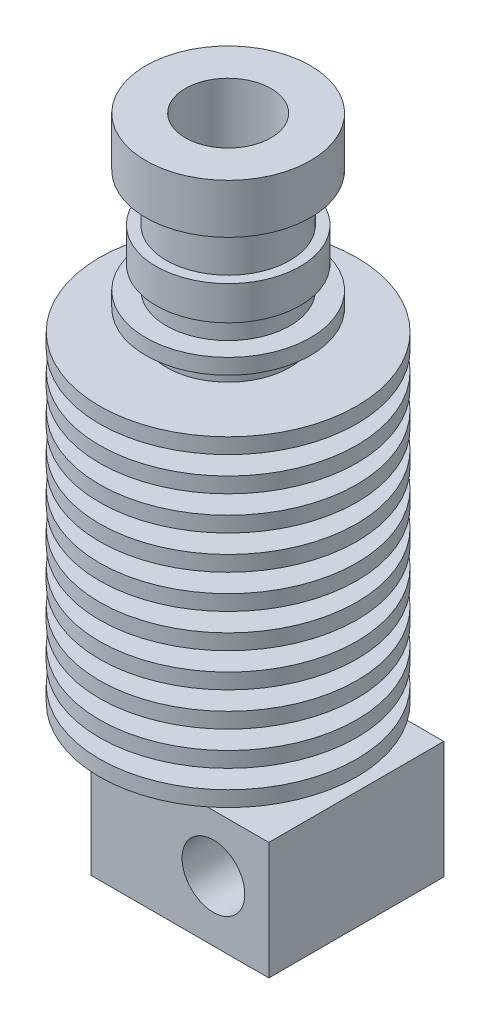
SolidWorks part; units mm, degrees
ref_plane "Front Plane" through (0, 0, 0) normal (0, 0, 1) x (1, 0, 0)
ref_plane "Top Plane" through (0, 0, 0) normal (0, 1, 0) x (1, 0, 0)
ref_plane "Right Plane" through (0, 0, 0) normal (1, 0, 0) x (0, 0, -1)
sketch "Sketch1" plane through (0, 0, 0) normal (0, 0, 1) x (1, 0, 0)
  line L0 (0, -1005.6554) -> (0, 48994.3446) construction
  line L1 (-2, -15.9255) -> (-2, -28.8164)
  line L2 (-8, 28.8745) -> (-6, 28.8745)
  line L3 (-8, 33.6745) -> (0, 33.6745)
  line L4 (-8, 33.6745) -> (-8, 28.8745)
  line L5 (-4, -32.8366) -> (-0.943, -34.9981)
  line L6 (0, 33.6745) -> (0, -33.6745)
  line L7 (-6, 28.8745) -> (-6, 24.2745)
  line L8 (-6, 24.2745) -> (-7, 24.2745)
  line L9 (-7, 24.2745) -> (-7, 20.9745)
  line L10 (-7, 20.9745) -> (-6, 20.9745)
  line L11 (-6, 20.9745) -> (-6, 18.7745)
  line L12 (-6, 18.7745) -> (-8, 18.7745)
  line L13 (-8, 18.7745) -> (-8, 17.2745)
  line L14 (-8, 17.2745) -> (-6, 17.2745)
  line L15 (-6, 17.2745) -> (-6, 15.2745)
  line L16 (-6, 15.2745) -> (-12.5, 15.2745)
  line L17 (-12.5, 15.2745) -> (-12.5, 13.7745)
  line L18 (-12.5, 13.7745) -> (-7.5, 13.7745)
  line L19 (-7.5, 13.7745) -> (-7.5, 11.9745)
  line L20 (-7.5, 11.9745) -> (-12.5, 11.9745)
  line L21 (-12.5, 11.9745) -> (-12.5, 10.4745)
  line L22 (-12.5, 10.4745) -> (-7.5, 10.4745)
  line L23 (-7.5, 10.4745) -> (-7.5, 8.6745)
  line L24 (-7.5, 8.6745) -> (-12.5, 8.6745)
  line L25 (-12.5, 8.6745) -> (-12.5, 7.1745)
  line L26 (-12.5, 7.1745) -> (-7.5, 7.1745)
  line L27 (-7.5, 7.1745) -> (-7.5, 5.3745)
  line L28 (-7.5, 5.3745) -> (-12.5, 5.3745)
  line L29 (-12.5, 5.3745) -> (-12.5, 3.8745)
  line L30 (-12.5, 3.8745) -> (-7.5, 3.8745)
  line L31 (-7.5, 3.8745) -> (-7.5, 2.0745)
  line L32 (-7.5, 2.0745) -> (-12.5, 2.0745)
  line L33 (-12.5, 2.0745) -> (-12.5, 0.5745)
  line L34 (-12.5, 0.5745) -> (-7.5, 0.5745)
  line L35 (-7.5, 0.5745) -> (-7.5, -1.2255)
  line L36 (-7.5, -1.2255) -> (-12.5, -1.2255)
  line L37 (-12.5, -1.2255) -> (-12.5, -2.7255)
  line L38 (-12.5, -2.7255) -> (-7.5, -2.7255)
  line L39 (-7.5, -2.7255) -> (-7.5, -4.5255)
  line L40 (-7.5, -4.5255) -> (-12.5, -4.5255)
  line L41 (-12.5, -4.5255) -> (-12.5, -6.0255)
  line L42 (-12.5, -6.0255) -> (-7.5, -6.0255)
  line L43 (-7.5, -6.0255) -> (-7.5, -7.8255)
  line L44 (-7.5, -7.8255) -> (-12.5, -7.8255)
  line L45 (-12.5, -7.8255) -> (-12.5, -9.3255)
  line L46 (-12.5, -9.3255) -> (-7.5, -9.3255)
  line L47 (-7.5, -9.3255) -> (-7.5, -11.1255)
  line L48 (-7.5, -11.1255) -> (-12.5, -11.1255)
  line L49 (-12.5, -11.1255) -> (-12.5, -12.6255)
  line L50 (-12.5, -12.6255) -> (-7.5, -12.6255)
  line L51 (-7.5, -12.6255) -> (-7.5, -14.4255)
  line L52 (-7.5, -14.4255) -> (-12.5, -14.4255)
  line L53 (-12.5, -14.4255) -> (-12.5, -15.9255)
  line L54 (-12.5, -15.9255) -> (-2, -15.9255)
  line L55 (-0.25, -33.6745) -> (0, -33.6745)
  line L56 (-0.25, -34.9981) -> (-0.25, -33.6745)
  line L57 (-0.943, -34.9981) -> (-0.25, -34.9981)
  line L58 (-4, -28.8164) -> (-4, -32.8366)
  line L59 (-2, -28.8164) -> (-4, -28.8164)
  dimension "D1" = 8
  dimension "D3" = 4.8
  dimension "D4" = 4.6
  dimension "D5" = 12.5
  dimension "D6" = 3.3
  dimension "D7" = 2.2
  dimension "D8" = 1.5
  dimension "D9" = 2
  dimension "D10" = 1.5
  dimension "D11" = 6
  dimension "D12" = 7
  dimension "D13" = 8
  dimension "D14" = 6
  dimension "D15" = 6
  dimension "D16" = 7.5
  dimension "D17" = 1.8
  dimension "D18" = 2
  dimension "D19" = 0.5
  dimension "D20" = 4
revolve "Revolve1" add sketch "Sketch1" angle 360 about L0
sketch "Sketch2" plane through (0, 33.6745, 0) normal (0, 1, 0) x (1, 0, 0)
  circle A0 centre (0, 0) radius 4.1593
  circle A1 centre (0, 0) radius 8 construction
  dimension "D1" = 8.3185
extrude "Cut-Extrude1" cut sketch "Sketch2" against normal blind 10
sketch "Sketch3" plane through (0, 0, 0) normal (0, 0, 1) x (1, 0, 0)
  line L1 (-4.8425, -17.2184) -> (12.4515, -17.2184)
  line L2 (-4.8425, -17.2184) -> (-4.8425, -28.6286)
  line L3 (-4.8425, -28.6286) -> (12.4515, -28.6286)
  line L4 (12.4515, -17.2184) -> (12.4515, -28.6286)
  dimension "D1" = 12.4515
  dimension "D2" = 4.8425
  dimension "D3" = 17.2184
  dimension "D4" = 28.6286
extrude "Boss-Extrude1" add sketch "Sketch3" along normal mid plane 17
sketch "Sketch4" plane through (0, 0, 8.5) normal (0, 0, 1) x (1, 0, 0)
  circle A0 centre (7.0661, -22.7504) radius 3.0487
extrude "Cut-Extrude2" cut sketch "Sketch4" against normal blind 17
